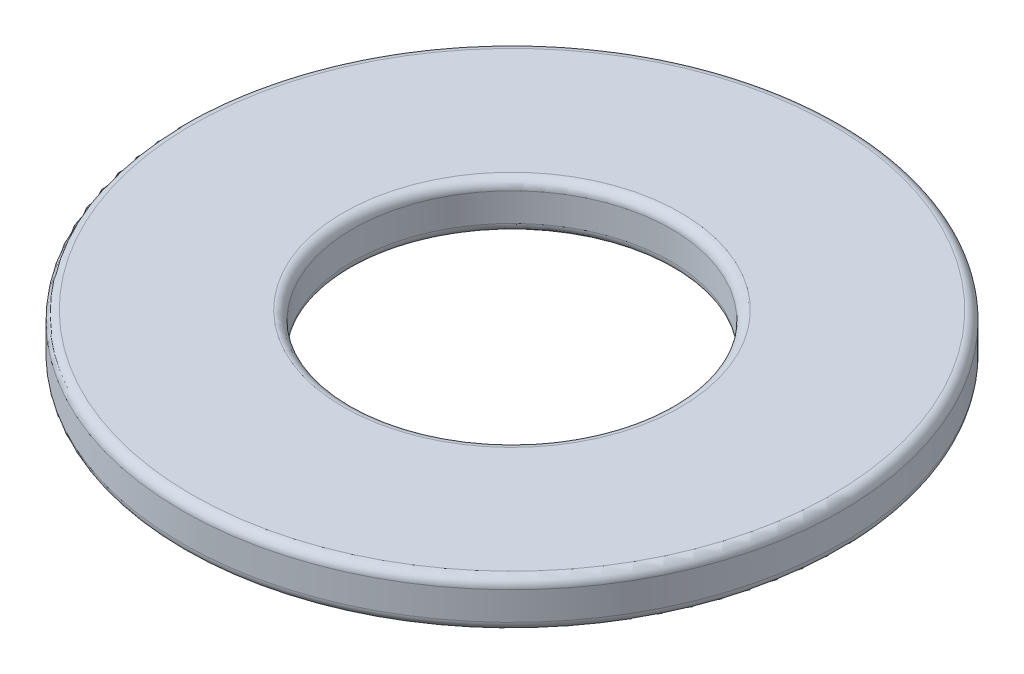
SolidWorks part; units mm, degrees
ref_plane "前视基准面" through (0, 0, 0) normal (0, 0, 1) x (1, 0, 0)
ref_plane "上视基准面" through (0, 0, 0) normal (0, 1, 0) x (1, 0, 0)
ref_plane "右视基准面" through (0, 0, 0) normal (1, 0, 0) x (0, 0, -1)
sketch "草图1" plane through (0, 0, 0) normal (0, 1, 0) x (1, 0, 0)
  circle A0 centre (0, 0) radius 3.5
  circle A1 centre (0, 0) radius 1.69
  dimension "D1" = 3.38
  dimension "D2" = 7
extrude "凸台-拉伸1" add sketch "草图1" along normal blind 0.5
fillet "圆角1" radius 0.1 4 edges at (0, 0, 1.69) (0, 0, 3.5) (0, 0.5, 1.69) (0, 0.5, 3.5)
